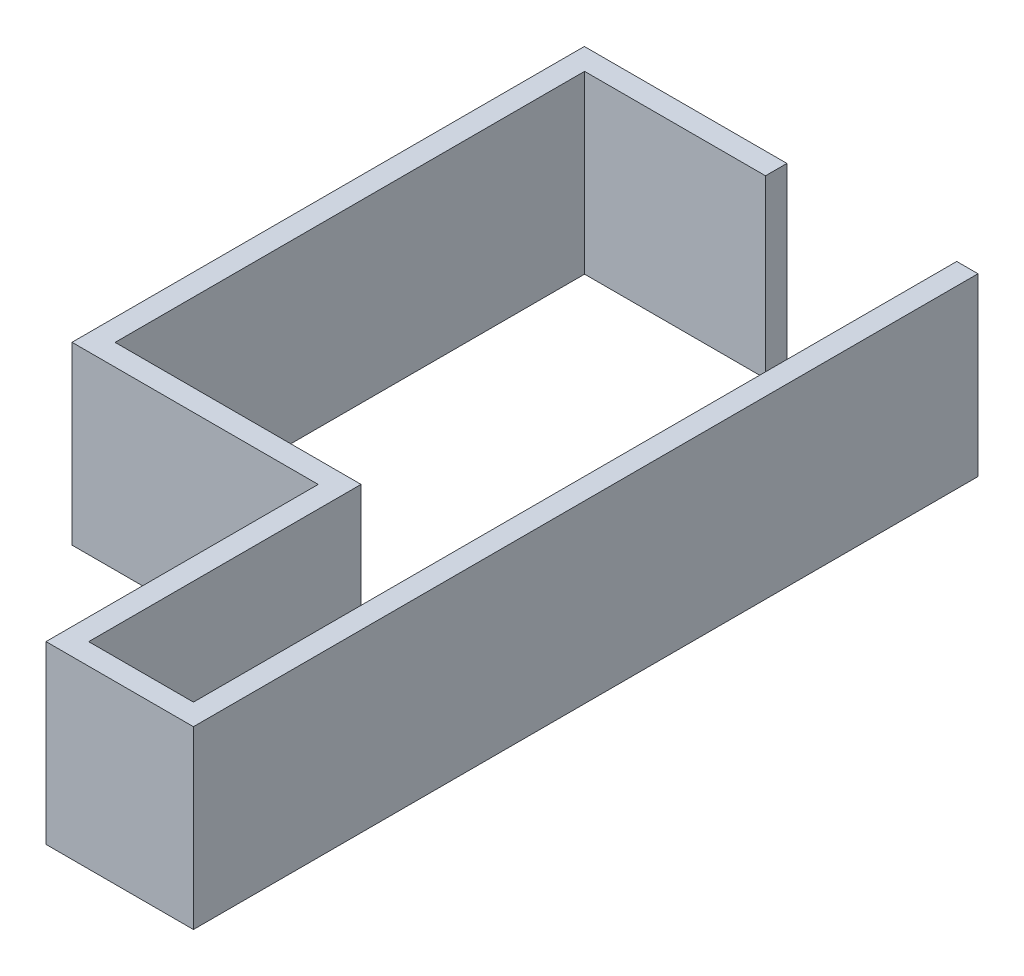
SolidWorks part; units mm, degrees
ref_plane "Front Plane" through (0, 0, 0) normal (0, 0, 1) x (1, 0, 0)
ref_plane "Top Plane" through (0, 0, 0) normal (0, 1, 0) x (1, 0, 0)
ref_plane "Right Plane" through (0, 0, 0) normal (1, 0, 0) x (0, 0, -1)
sketch "Sketch1" plane through (0, 0, 0) normal (0, 1, 0) x (1, 0, 0)
  line L0 (-6.25, 27.4) -> (-17.0269, 27.4)
  line L1 (-6.25, 27.3) -> (-6.25, 27.4)
  line L2 (-16.9, 27.1119) -> (-17, 27.1119)
  line L4 (-17, 27.1119) -> (-17, 27.4)
  line L5 (-17, 27.1119) -> (-17, -27.3874)
  line L6 (-17, -27.3874) -> (11.7033, -27.3874)
  line L7 (11.7033, -27.3874) -> (11.7033, -59.1724)
  line L8 (11.7033, -59.1724) -> (23.9286, -59.1724)
  line L9 (23.9286, -59.1724) -> (23.9286, 27.4)
  line L10 (4.1112, 27.4) -> (-6.25, 27.4)
  line L11 (23.9286, 27.4) -> (23.9286, 29.9)
  line L12 (-6.25, 29.9) -> (-17.0269, 29.9)
  line L13 (-17.0269, 29.9) -> (-19.5264, 29.9)
  line L14 (-19.5264, 29.9) -> (-19.5264, -27.3874)
  line L15 (-19.5264, -27.3874) -> (-19.5264, -29.8915)
  line L16 (-19.5264, -29.8915) -> (9.2053, -29.8915)
  line L17 (4.1112, 29.9) -> (4.1112, 27.4)
  line L18 (9.2053, -29.8915) -> (9.2053, -59.1724)
  line L19 (9.2053, -59.1724) -> (9.2053, -61.6565)
  line L20 (9.2053, -61.6565) -> (23.9286, -61.6565)
  line L21 (23.9286, -61.6565) -> (26.4102, -61.6565)
  line L22 (26.4102, -61.6565) -> (26.4102, 29.9)
  line L23 (26.4102, 29.9) -> (23.9286, 29.9)
  line L24 (4.1112, 29.9) -> (-6.25, 29.9)
extrude "Boss-Extrude1" add sketch "Sketch1" along normal blind 20.5
